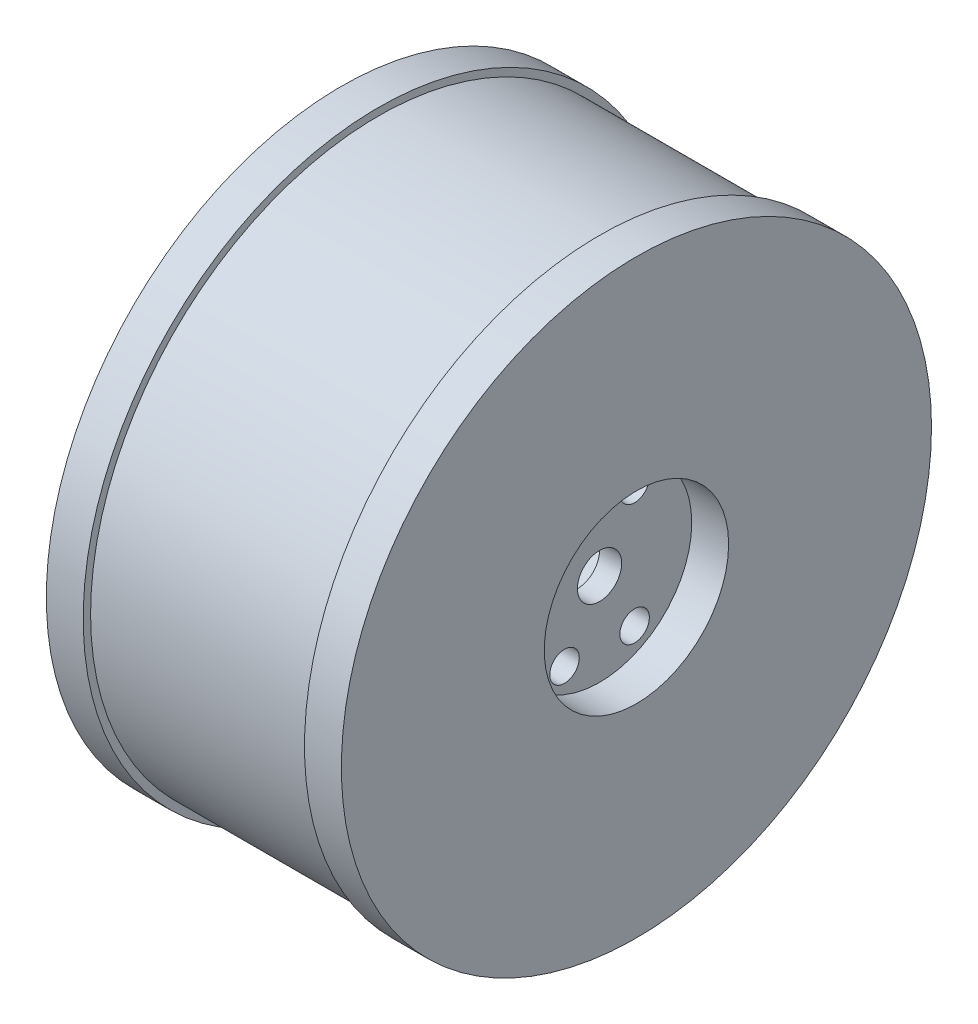
SolidWorks part; units mm, degrees
ref_plane "Plan de face" through (0, 0, 0) normal (0, 0, 1) x (1, 0, 0)
ref_plane "Plan de dessus" through (0, 0, 0) normal (0, 1, 0) x (1, 0, 0)
ref_plane "Plan de droite" through (0, 0, 0) normal (1, 0, 0) x (0, 0, -1)
sketch "Esquisse1" plane through (0, 0, 0) normal (0, 0, 1) x (1, 0, 0)
  line L0 (-49.6445, 0) -> (53.9199, 0) construction
  line L1 (0, 34) -> (0, 0)
  line L2 (0, 34) -> (-32, 34)
  line L3 (-32, 34) -> (-32, 40)
  line L4 (-32, 40) -> (-27, 40)
  line L5 (-27, 40) -> (-27, 39)
  line L6 (-27, 39) -> (3, 39)
  line L7 (3, 39) -> (3, 40)
  line L8 (3, 40) -> (8, 40)
  line L9 (8, 40) -> (8, 0)
  line L13 (0, 0) -> (8, 0)
  dimension "D2" = 5
  dimension "D3" = 5
  dimension "D4" = 40
  dimension "D5" = 1
  dimension "D6" = 8
  dimension "D10" = 6
  dimension "D11" = 1
  dimension "D12" = 30
revolve "Révolution1" add sketch "Esquisse1" angle 360 about L0
sketch "Esquisse2" plane through (0, 0, 0) normal (0, 0, 1) x (1, 0, 0)
  line L3 (0, 0) -> (8, 0) construction
  line L11 (8, -40) -> (8, 40) construction
  line L12 (8, 0) -> (8, 12.5)
  line L13 (8, 12.5) -> (3, 12.5)
  line L14 (3, 12.5) -> (3, 0)
  line L15 (3, 0) -> (8, 0)
  dimension "D1" = 25
  dimension "D2" = 5
revolve "Enlèvement de matière-Révolution1" cut sketch "Esquisse2" angle 360 about L3
sketch "Esquisse3" plane through (3, 0, 0) normal (1, 0, 0) x (0, 0, -1)
  line L0 (0, 12.5) -> (0, 0) construction
  line L1 (0, 0) -> (12.5, 0) construction
  line L2 (4.75, 8.2272) -> (0, 0) construction
  circle A0 centre (4.75, 8.2272) radius 2
  circle A2 centre (0, 0) radius 12.5 construction
  circle A3 centre (0, 0) radius 12.5 construction
  circle A4 centre (-4.75, 8.2272) radius 2
  circle A5 centre (4.75, -8.2272) radius 2
  circle A6 centre (-4.75, -8.2272) radius 2
  dimension "D1" = 4
  dimension "D2" = 9.5
  dimension "D3" = 30
extrude "Enlèv. mat.-Extru.1" cut sketch "Esquisse3" against normal through all
sketch "Esquisse4" plane through (3, 0, 0) normal (1, 0, 0) x (0, 0, -1)
  circle A0 centre (0, 0) radius 3
  dimension "D1" = 6
extrude "Enlèv. mat.-Extru.2" cut sketch "Esquisse4" against normal through all
move or copy body "Body-Move/Copy1" bodies to move or copy 106
